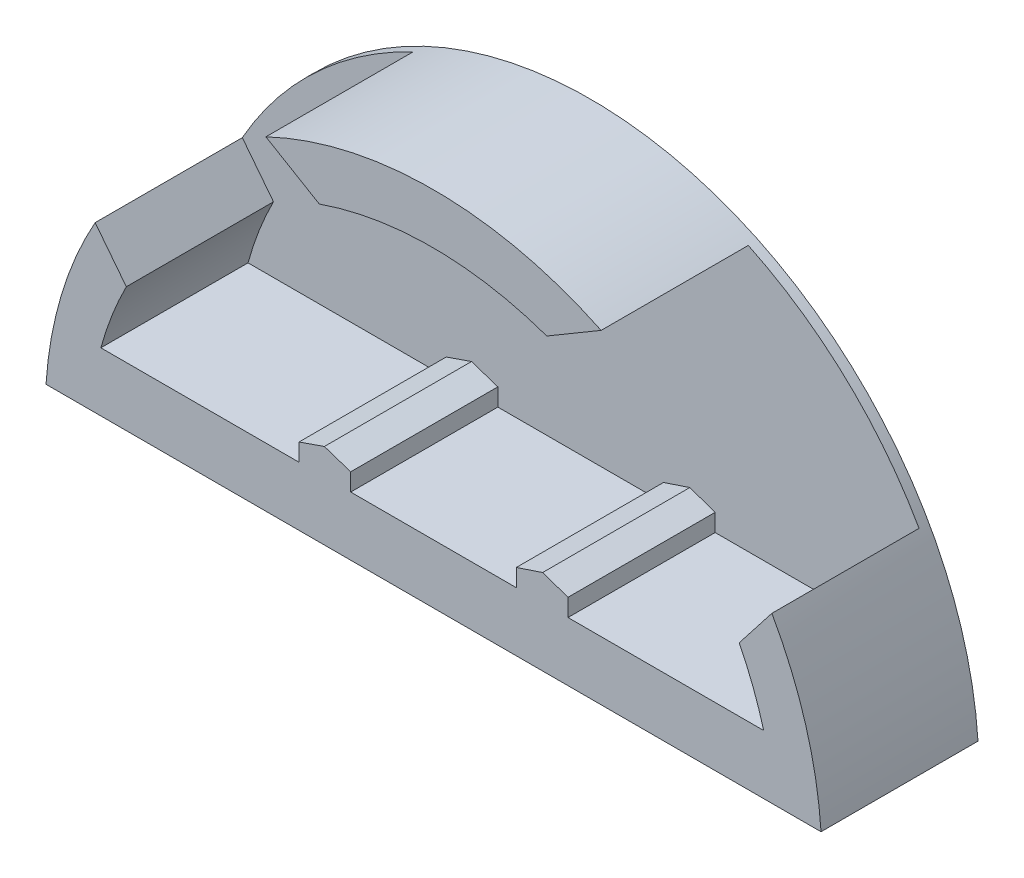
SolidWorks part; units mm, degrees
ref_plane "Front Plane" through (0, 0, 0) normal (0, 0, 1) x (1, 0, 0)
ref_plane "Top Plane" through (0, 0, 0) normal (0, 1, 0) x (1, 0, 0)
ref_plane "Right Plane" through (0, 0, 0) normal (1, 0, 0) x (0, 0, -1)
sketch "Sketch1" plane through (0, 0, 0) normal (0, 0, 1) x (1, 0, 0)
  line L2 (-6.6793, 1.2034) -> (-3.1908, 1.2034)
  line L4 (-3.1908, 1.2034) -> (-3.1908, 1.561)
  line L5 (-3.1908, 1.561) -> (-2.6742, 1.7398)
  line L6 (-2.6742, 1.7398) -> (-2.1377, 1.561)
  line L7 (-2.1377, 1.561) -> (-2.1377, 1.2034)
  line L8 (-2.1377, 1.2034) -> (1.2394, 1.2034)
  line L12 (-8.3491, 0) -> (7.4509, 0)
  line L14 (1.2394, 1.561) -> (1.2394, 1.2034)
  line L15 (1.7759, 1.7398) -> (1.2394, 1.561)
  line L16 (2.2926, 1.561) -> (1.7759, 1.7398)
  line L17 (2.2926, 1.2034) -> (2.2926, 1.561)
  line L18 (5.781, 1.2034) -> (2.2926, 1.2034)
  arc A5 (-8.3491, 0) -> (7.4509, 0) centre (-0.4491, -0.5317) cw
  arc A6 (-6.6793, 1.2034) -> (5.781, 1.2034) centre (-0.4491, -0.4742) cw
  dimension "D1" = 15.8
extrude "Boss-Extrude1" add sketch "Sketch1" along normal blind 3.2
ref_plane "Plane1" through (0, 0, 3.2) normal (0, 0, 1) x (1, 0, 0)
sketch "Sketch3" plane through (0, 0, 3.2) normal (0, 0, 1) x (1, 0, 0)
  line L0 (-3.1908, 1.2034) -> (-3.1908, 1.561)
  line L1 (-3.1908, 1.2034) -> (-7.2306, 1.2034)
  line L2 (-3.1908, 1.561) -> (-2.6742, 1.7398)
  line L3 (-2.6742, 1.7398) -> (-2.1377, 1.561)
  line L4 (-2.1377, 1.561) -> (-2.1377, 1.2034)
  line L5 (-2.1377, 1.2034) -> (1.2394, 1.2034)
  line L6 (1.2394, 1.2034) -> (1.2394, 1.561)
  line L7 (2.2926, 1.2034) -> (6.2819, 1.2034)
  line L8 (1.2394, 1.561) -> (1.7759, 1.7398)
  line L9 (1.7759, 1.7398) -> (2.2926, 1.561)
  line L10 (2.2926, 1.561) -> (2.2926, 1.2034)
  arc A6 (-7.2306, 1.2034) -> (6.2819, 1.2034) centre (-0.4743, -0.6473) cw
extrude "Cut-Extrude1" cut sketch "Sketch3" against normal blind 3
ref_plane "Plane2" through (0, 0, 3.2) normal (0, 0, 1) x (1, 0, 0)
sketch "Sketch6" plane through (0, 0, 3.2) normal (0, 0, 1) x (1, 0, 0)
  line L0 (-3.8664, 6.6108) -> (-2.7774, 5.9684)
  line L1 (-6.7116, 2.5414) -> (-7.3469, 3.3559)
  line L2 (-0.4491, 0) -> (-0.4491, 1.2034) construction
  line L3 (-8.3491, 0) -> (7.4509, 0) construction
  line L4 (-2.1377, 1.2034) -> (1.2394, 1.2034) construction
  line L5 (5.7782, 2.4963) -> (6.4487, 3.3559)
  line L6 (2.9681, 6.6108) -> (1.855, 5.9542)
  arc A0 (6.2819, 1.2034) -> (-7.2306, 1.2034) centre (-0.4743, -0.6473) ccw construction
  arc A1 (7.4509, 0) -> (-8.3491, 0) centre (-0.4491, -0.5317) ccw construction
  arc A2 (6.2819, 1.2034) -> (-7.2306, 1.2034) centre (-0.4743, -0.6473) ccw construction
  arc A3 (-6.7116, 2.5414) -> (-2.7774, 5.9684) centre (-0.4152, -0.7151) cw
  arc A4 (-7.3469, 3.3559) -> (-3.8664, 6.6108) centre (-0.4491, -0.5317) cw
  arc A6 (6.4487, 3.3559) -> (2.9681, 6.6108) centre (-0.4491, -0.5317) ccw
  arc A7 (5.7782, 2.4963) -> (1.855, 5.9542) centre (-0.4245, -0.5867) ccw
extrude "Cut-Extrude2" cut sketch "Sketch6" against normal blind 3
